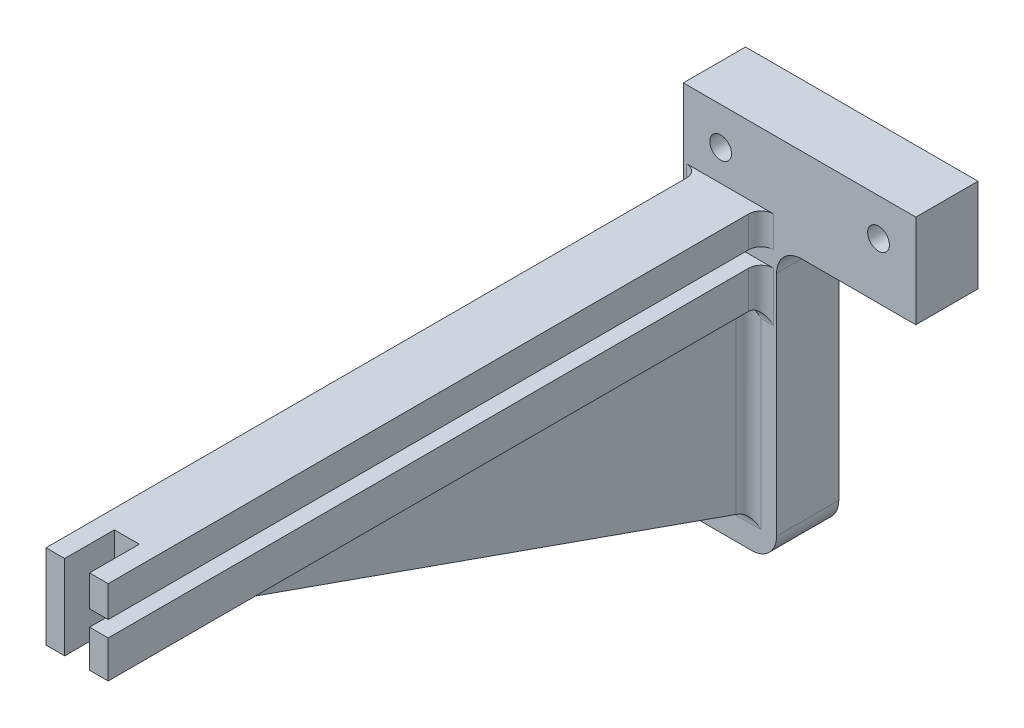
SolidWorks part; units mm, degrees
ref_plane "Front Plane" through (0, 0, 0) normal (0, 0, 1) x (1, 0, 0)
ref_plane "Top Plane" through (0, 0, 0) normal (0, 1, 0) x (1, 0, 0)
ref_plane "Right Plane" through (0, 0, 0) normal (1, 0, 0) x (0, 0, -1)
sketch "Sketch1" plane through (0, 0, 0) normal (0, 0, 1) x (1, 0, 0)
  line L0 (0, 0) -> (0, 15)
  line L1 (0, 15) -> (15, 15)
  line L2 (15, 15) -> (15, 59.64)
  line L3 (15, 59.64) -> (52.39, 59.64)
  line L4 (52.39, 59.64) -> (52.39, 44.64)
  line L5 (52.39, 44.64) -> (30, 44.64)
  line L6 (30, 44.64) -> (30, 0)
  line L7 (30, 0) -> (0, 0)
  circle A0 centre (6.39, 7.5) radius 1.75
  circle A1 centre (21, 53.64) radius 1.75
  circle A2 centre (46.39, 53.64) radius 1.75
  point P17 (0, 7.5)
  dimension "D2" = 3.5
  dimension "D1" = 6
  dimension "D3" = 25.39
  dimension "D4" = 14.61
  dimension "D5" = 46.14
  dimension "D6" = 15
  dimension "D7" = 15
  dimension "D8" = 6
  dimension "D9" = 6
  dimension "D10" = 15
  dimension "D11" = 30
extrude "Boss-Extrude1" add sketch "Sketch1" along normal blind 10
sketch "Sketch2" plane through (0, 0, 10) normal (0, 0, 1) x (1, 0, 0)
  line L0 (27.5, 48.64) -> (17.5, 48.64)
  line L1 (17.5, 48.64) -> (17.5, 35.08)
  line L2 (17.5, 35.08) -> (27.5, 35.08)
  line L3 (27.5, 35.08) -> (27.5, 41.08)
  line L4 (27.5, 41.08) -> (22.478, 41.08)
  line L5 (22.478, 41.08) -> (22.478, 43.64)
  line L6 (22.478, 43.64) -> (27.5, 43.64)
  line L7 (27.5, 43.64) -> (27.5, 48.64)
  line L8 (15, 59.64) -> (15, 15) construction
  circle A0 centre (21, 53.64) radius 1.75 construction
  dimension "D7" = 5
  dimension "D1" = 2.56
  dimension "D2" = 5
  dimension "D3" = 6
  dimension "D4" = 10
  dimension "D5" = 5.022
  dimension "D6" = 2.5
extrude "Boss-Extrude2" add sketch "Sketch2" along normal blind 105
ref_plane "Plane1" through (22.5, 0, 0) normal (1, 0, 0) x (0, 0, -1)
sketch "Sketch3" plane through (22.5, 0, 0) normal (1, 0, 0) x (0, 0, -1)
  line L0 (-10, 5.08) -> (-95, 35.08)
  line L1 (-10, 55.39) -> (-10, 51.89) construction
  line L2 (-115, 35.08) -> (-10, 35.08) construction
  dimension "D1" = 30
  dimension "D2" = 85
rib "Rib1" sketch "Sketch3" sketch "Sketch3" thickness 6 extrusion direction parallel to sketch draft on no parameters "D1"=6
fillet "Fillet1" radius 4 3 edges at (30, 0, 5) (30, 44.64, 5) (15, 15, 5)
fillet "Fillet2" radius 2 8 edges at (27.5, 46.14, 10) (27.5, 38.08, 10) (26.5, 35.08, 10) (25.5, 20.08, 10) (19.5, 20.08, 10) (18.5, 35.08, 10) (17.5, 41.86, 10) (22.5, 5.08, 10)
sketch "Sketch4" plane through (0, 0, 115) normal (0, 0, 1) x (1, 0, 0)
  line L0 (17.5, 35.08) -> (27.5, 35.08) construction
  line L1 (20.5, 35.08) -> (24.5, 35.08)
  line L2 (20.5, 35.08) -> (20.5, 48.64)
  line L3 (20.5, 48.64) -> (24.5, 48.64)
  line L4 (24.5, 35.08) -> (24.5, 48.64)
  line L5 (27.5, 48.64) -> (17.5, 48.64) construction
  line L6 (27.5, 35.08) -> (27.5, 41.08) construction
  line L7 (17.5, 48.64) -> (17.5, 35.08) construction
  dimension "D1" = 3
  dimension "D2" = 3
extrude "Cut-Extrude1" cut sketch "Sketch4" against normal blind 8
